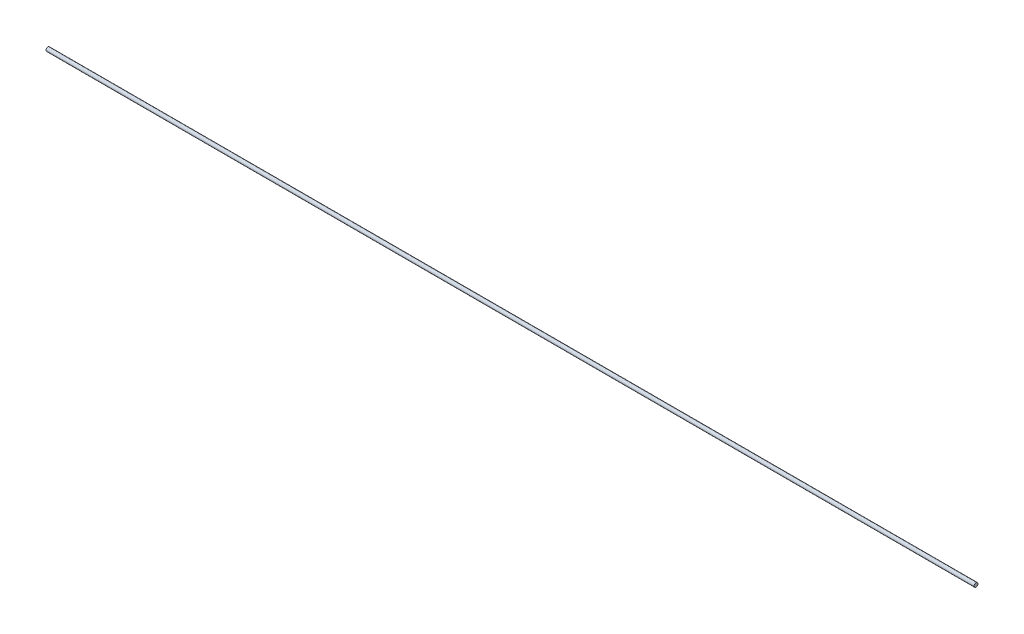
SolidWorks part; units mm, degrees
material "Thornel Mat VMA"
ref_plane "Front" through (0, 0, 0) normal (0, 0, 1) x (1, 0, 0)
ref_plane "Top" through (0, 0, 0) normal (0, 1, 0) x (1, 0, 0)
ref_plane "Right" through (0, 0, 0) normal (1, 0, 0) x (0, 0, -1)
sketch "Sketch1" plane through (0, 0, 0) normal (1, 0, 0) x (0, 0, -1)
  circle A0 centre (0, 0) radius 3.175
  dimension "D1" = 6.35
extrude "Boss-Extrude1" add sketch "Sketch1" along normal blind 1524 contours A0
